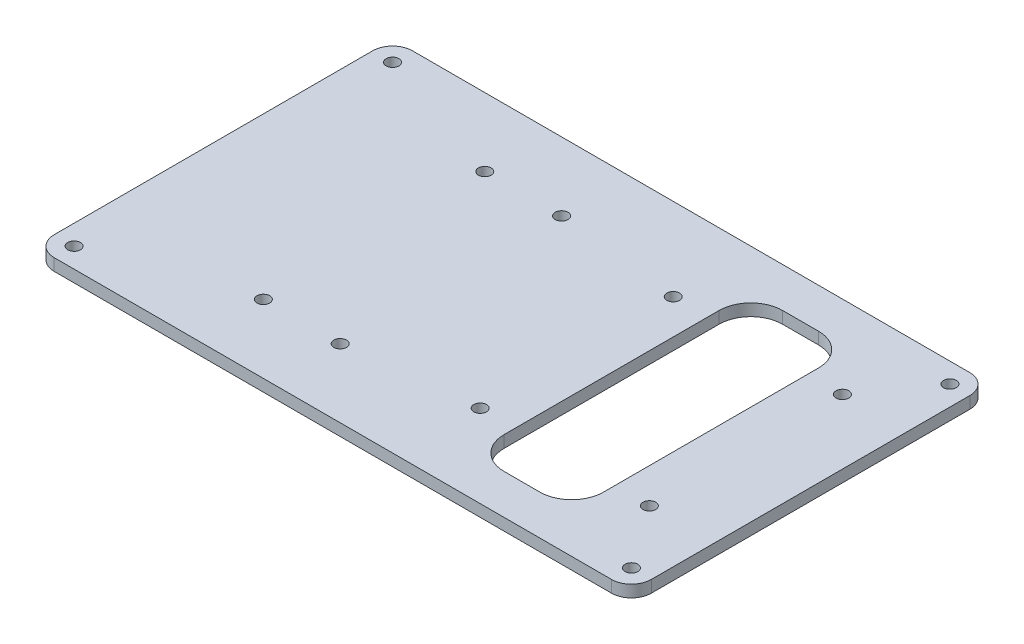
SolidWorks part; units mm, degrees
ref_plane "Front Plane" through (0, 0, 0) normal (0, 0, 1) x (1, 0, 0)
ref_plane "Top Plane" through (0, 0, 0) normal (0, 1, 0) x (1, 0, 0)
ref_plane "Right Plane" through (0, 0, 0) normal (1, 0, 0) x (0, 0, -1)
sketch "Sketch1" plane through (0, 0, 0) normal (0, 1, 0) x (1, 0, 0)
  line L0 (-75, 0) -> (75, 0) construction
  line L1 (-70, 45) -> (70, 45)
  line L2 (-75, 40) -> (-75, -40)
  line L3 (-70, -45) -> (70, -45)
  line L4 (75, 40) -> (75, -40)
  line L5 (-75, 45) -> (75, -45) construction
  line L6 (-75, -45) -> (75, 45) construction
  line L7 (0, 45) -> (0, -45) construction
  line L8 (37.5, 45) -> (37.5, -45) construction
  line L9 (-45.105, 38.85) -> (-4.895, 38.85) construction
  line L10 (-45.105, 38.85) -> (-45.105, -38.85) construction
  line L11 (-45.105, -38.85) -> (-4.895, -38.85) construction
  line L12 (-4.895, 38.85) -> (-4.895, -38.85) construction
  line L13 (-45.105, 38.85) -> (-4.895, -38.85) construction
  line L14 (-45.105, -38.85) -> (-4.895, 38.85) construction
  line L15 (-25, 38.85) -> (-25, -38.85) construction
  line L16 (33, 35) -> (42, 35)
  line L17 (25, 27) -> (25, -27)
  line L18 (33, -35) -> (42, -35)
  line L19 (50, 27) -> (50, -27)
  line L20 (25, 35) -> (50, -35) construction
  line L21 (25, -35) -> (50, 35) construction
  arc A0 (-70, 45) -> (-75, 40) centre (-70, 40) ccw
  arc A1 (-75, -40) -> (-70, -45) centre (-70, -40) ccw
  arc A2 (70, -45) -> (75, -40) centre (70, -40) ccw
  arc A3 (75, 40) -> (70, 45) centre (70, 40) ccw
  circle A8 centre (16.25, 24.25) radius 1.6
  circle A9 centre (58.75, 24.25) radius 1.6
  circle A10 centre (58.75, -24.25) radius 1.6
  circle A11 centre (16.25, -24.25) radius 1.6
  arc A12 (42, 35) -> (50, 27) centre (42, 27) cw
  arc A13 (50, -27) -> (42, -35) centre (42, -27) cw
  arc A14 (33, -35) -> (25, -27) centre (33, -27) cw
  arc A15 (25, 27) -> (33, 35) centre (33, 27) cw
  circle A16 centre (-34.65, 27.81) radius 1.6
  circle A17 centre (-15.35, 27.81) radius 1.6
  circle A18 centre (-15.35, -27.81) radius 1.6
  circle A19 centre (-34.65, -27.81) radius 1.6
  circle A20 centre (-70, 40) radius 1.6
  circle A21 centre (-70, -40) radius 1.6
  circle A22 centre (70, 40) radius 1.6
  circle A23 centre (70, -40) radius 1.6
  point P0 (0, 0)
  point P30 (-25, 0)
  point P37 (37.5, 0)
  dimension "D3" = 5
  dimension "D4" = 37.5
  dimension "D10" = 3.2
  dimension "D13" = 8
  dimension "D14" = 3.2
  dimension "D17" = 3.2
  dimension "D1" = 90
  dimension "D2" = 150
  dimension "D5" = 21.25
  dimension "D6" = 24.25
  dimension "D7" = 50
  dimension "D8" = 77.7
  dimension "D9" = 40.21
  dimension "D11" = 70
  dimension "D12" = 25
  dimension "D15" = 27.81
  dimension "D16" = 9.65
extrude "Boss-Extrude2" add sketch "Sketch1" along normal blind 3
